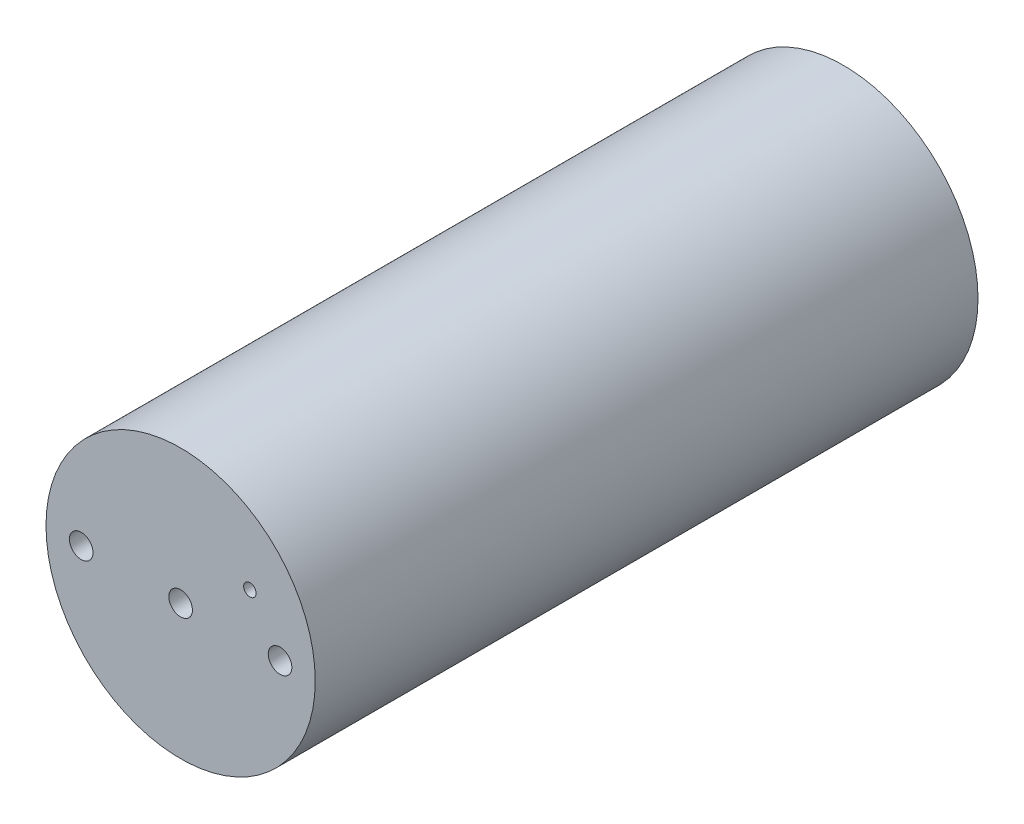
SolidWorks part; units mm, degrees
ref_plane "前视基准面" through (0, 0, 0) normal (0, 0, 1) x (1, 0, 0)
ref_plane "上视基准面" through (0, 0, 0) normal (0, 1, 0) x (1, 0, 0)
ref_plane "右视基准面" through (0, 0, 0) normal (1, 0, 0) x (0, 0, -1)
sketch "e-bay Shell" plane through (0, 0, 0) normal (0, 0, 1) x (1, 0, 0)
  circle A0 centre (0, 0) radius 41.275
  circle A1 centre (0, 0) radius 38.1
  dimension "D1" = 76.2
  dimension "D2" = 82.55
extrude "Boss-Extrude1" add sketch "e-bay Shell" along normal blind 203.2
sketch "Sketch2" plane through (0, 0, 203.2) normal (0, 0, 1) x (1, 0, 0)
  line L0 (0, 38.1) -> (0, -38.1) construction
  circle A0 centre (0, 0) radius 38.1
  circle A1 centre (0, 0) radius 3.6195
  circle A2 centre (-30.48, 0) radius 3.6195
  circle A3 centre (21.232, 14.2121) radius 1.905
  circle A4 centre (30.48, 0) radius 3.6195
  point P8 (0, 0)
  dimension "D1" = 76.2
  dimension "D2" = 7.239
  dimension "D3" = 3.81
  dimension "D4" = 7.239
  dimension "D5" = 30.48
extrude "lid-top" add sketch "Sketch2" against normal blind 6.35
ref_plane "Plane1" through (0, 0, 101.6) normal (0, 0, 1) x (1, 0, 0)
mirror "Mirror3" about plane through (0, 0, 101.6) normal (0, 0, 1) of "lid-top"
